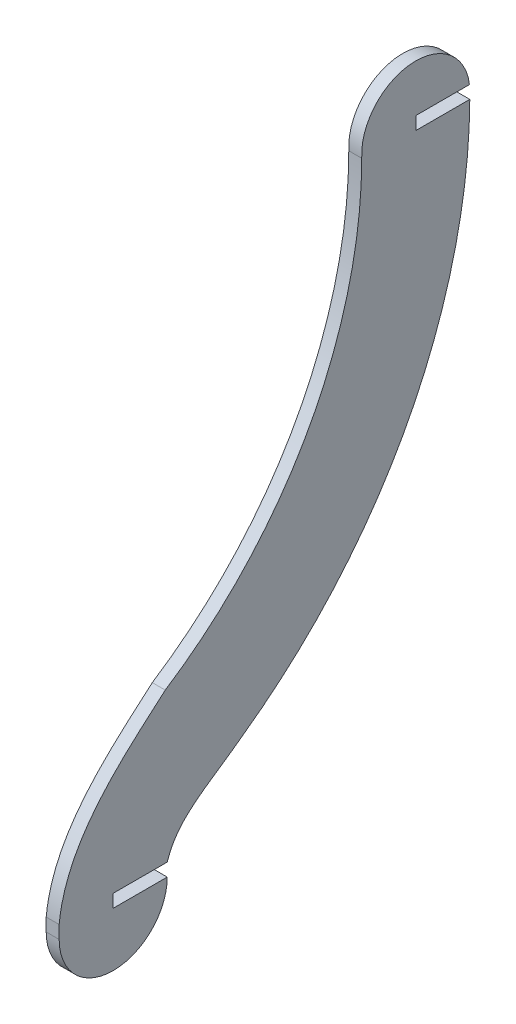
SolidWorks part; units mm, degrees
ref_plane "Front Plane" through (0, 0, 0) normal (0, 0, 1) x (1, 0, 0)
ref_plane "Top Plane" through (0, 0, 0) normal (0, 1, 0) x (1, 0, 0)
ref_plane "Right Plane" through (0, 0, 0) normal (1, 0, 0) x (0, 0, -1)
sketch "Sketch1" plane through (0, 0, 0) normal (1, 0, 0) x (0, 0, -1)
  line L0 (54.5436, -83.8153) -> (30, -118.5) construction
  line L5 (-125, 1.5) -> (125, 1.5) construction
  line L6 (-125, 1.5) -> (-125, -1.5) construction
  line L7 (-125, -1.5) -> (125, -1.5) construction
  line L8 (125, 1.5) -> (125, -1.5) construction
  line L9 (-125, 1.5) -> (125, -1.5) construction
  line L10 (-125, -1.5) -> (125, 1.5) construction
  line L11 (-55, -121.5) -> (55, -121.5) construction
  line L12 (-55, -121.5) -> (-55, -118.5) construction
  line L13 (-55, -118.5) -> (55, -118.5) construction
  line L14 (55, -121.5) -> (55, -118.5) construction
  line L15 (-55, -121.5) -> (55, -118.5) construction
  line L16 (-55, -118.5) -> (55, -121.5) construction
  line L17 (72.3473, -101.9356) -> (50.4075, -132.9407) construction
  line L18 (125, 0) -> (125, 1.5)
  line L19 (55, -118.5) -> (55, -121.5)
  line L20 (30, -118.5) -> (30, -121.5)
  circle A0 centre (0, 0) radius 100 construction
  arc A1 (100, 0) -> (54.5436, -83.8153) centre (0, 0) cw
  arc A3 (125, 0) -> (72.3473, -101.9356) centre (0, 0) cw
  arc A5 (100, 0) -> (125, 1.5) centre (112.5, 0.75) cw
  arc A6 (55, -121.5) -> (30, -121.5) centre (42.5, -121.5) cw
  spline S0 degree 3 poles (54.5436, -83.8153) (44.4344, -92.6089) (31.5813, -102.9457) (30, -118.5) knots 0 0 0 0 1 1 1 1
  spline S1 degree 3 poles (55, -118.5) (57.3843, -110.8686) (64.5489, -107.8606) (72.3473, -101.9356) knots 0 0 0 0 1 1 1 1
  point P7 (0, -120)
  point P23 (0, 0)
  point P24 (31.8556, -121.5)
  point P25 (31.8556, -121.5)
  point P26 (0, 0)
  point P27 (29.6401, -121.5)
  dimension "D1" = 200
  dimension "D8" = 25
  dimension "D4" = 3
  dimension "D5" = 110
  dimension "D6" = 120
  dimension "D7" = 25
extrude "Boss-Extrude2" add sketch "Sketch1" along normal blind 3
sketch "Sketch2" plane through (3, 0, 0) normal (1, 0, 0) x (0, 0, -1)
  line L1 (125, -0.6908) -> (112.5, -0.6908)
  line L2 (125, -0.6908) -> (125, 2.3092)
  line L3 (125, 2.3092) -> (112.5, 2.3092)
  line L4 (112.5, -0.6908) -> (112.5, 2.3092)
  line L6 (55, -118.5) -> (42.5, -118.5)
  line L7 (55, -118.5) -> (55, -121.5)
  line L8 (55, -121.5) -> (42.5, -121.5)
  line L9 (42.5, -118.5) -> (42.5, -121.5)
  dimension "D1" = 12.5
  dimension "D2" = 3
  dimension "D3" = 12.5
  dimension "D4" = 3
extrude "Cut-Extrude1" cut sketch "Sketch2" against normal blind 3
